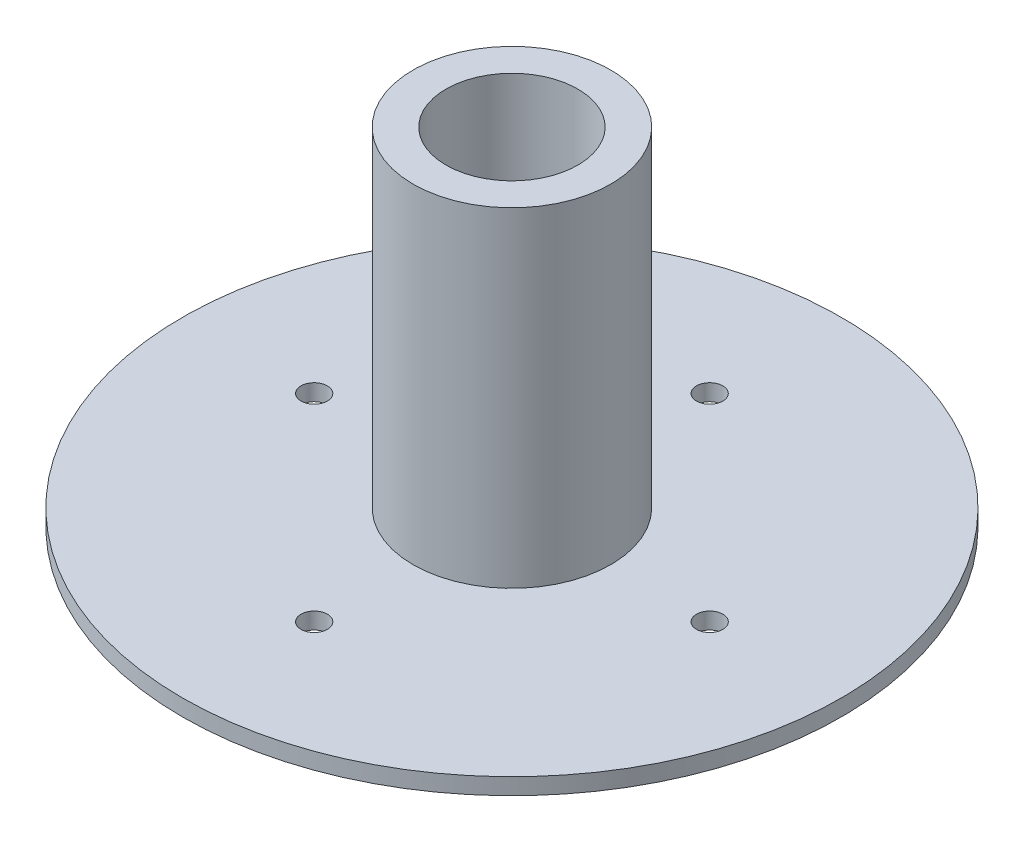
SolidWorks part; units mm, degrees
ref_plane "前视基准面" through (0, 0, 0) normal (0, 0, 1) x (1, 0, 0)
ref_plane "上视基准面" through (0, 0, 0) normal (0, 1, 0) x (1, 0, 0)
ref_plane "右视基准面" through (0, 0, 0) normal (1, 0, 0) x (0, 0, -1)
sketch "草图1" plane through (0, 0, 0) normal (0, 1, 0) x (1, 0, 0)
  circle A0 centre (0, 0) radius 100
extrude "凸台-拉伸1" add sketch "草图1" along normal blind 5
sketch "草图2" plane through (0, 5, 0) normal (0, 1, 0) x (1, 0, 0)
  line L0 (0, 105.2282) -> (0, -107.7804) construction
  line L3 (124.0741, 0) -> (-124.0527, 0) construction
  circle A0 centre (0, 0) radius 60
hole_wizard "大小mm 暗销孔2" positions "3D草图2" profile "草图5" hole size "Ø8.0" standard "ISO"
sketch3d "3D草图2"
  line L0 (0, 5, -105.2282) -> (0, 5, 107.7804) construction
  line L1 (124.0741, 5, 0) -> (-124.0527, 5, 0) construction
  circle A0 centre (0, 5, 0) radius 60 construction
  point P0 (0, 5, -60)
  point P4 (0, 65, 0)
  point P7 (-60, 5, 0)
  point P11 (0, 5, 60)
  point P13 (60, 5, 0)
sketch "草图5" plane through (0, 5, -60) normal (1, 0, 0) x (0, 0, 1)
  line L0 (0, 0) -> (0, 22.4034)
  line L1 (0, 22.4034) -> (4, 20)
  line L2 (4, 20) -> (4, 0)
  line L5 (4, 0) -> (0, 0)
  line L10 (0, 22.4034) -> (-4, 20) construction
  line L11 (0, -6.35) -> (0, 107.95) construction
  dimension "孔直径" = 8
  dimension "孔深度" = 20
  dimension "导头角度" = 118
sketch "草图6" plane through (0, 5, 0) normal (0, 1, 0) x (1, 0, 0)
  circle A0 centre (0, 0) radius 20
  circle A1 centre (0, 0) radius 30
extrude "凸台-拉伸2" add sketch "草图6" along normal blind 100
sketch "草图7" plane through (0, 0, 0) normal (0, 0, 1) x (1, 0, 0)
  line L0 (0, 159.3561) -> (0, -8.1599) construction
